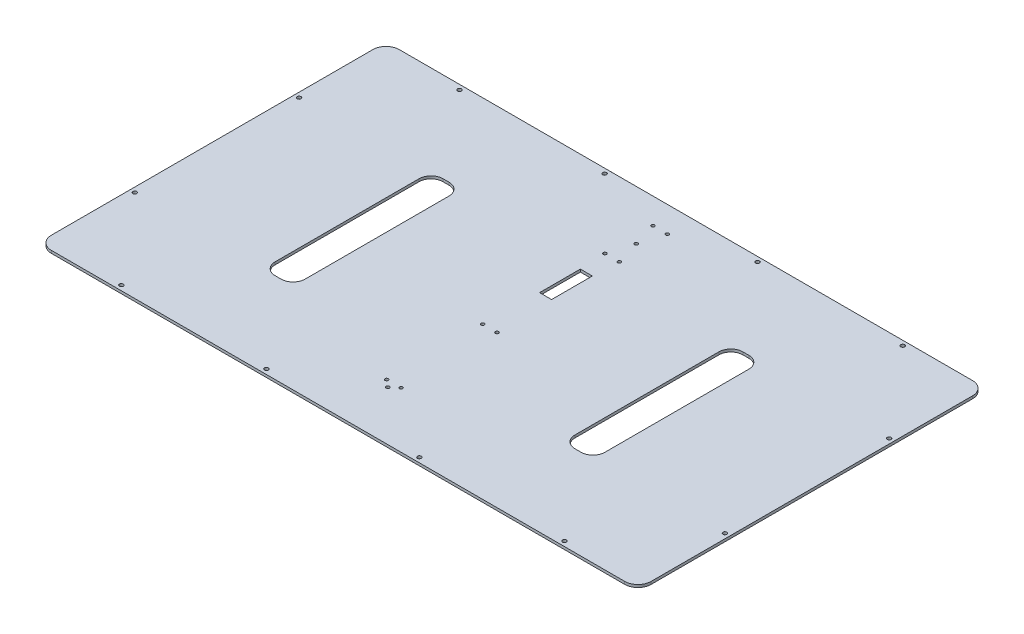
SolidWorks part; units mm, degrees
ref_plane "Front Plane" through (0, 0, 0) normal (0, 0, 1) x (1, 0, 0)
ref_plane "Top Plane" through (0, 0, 0) normal (0, 1, 0) x (1, 0, 0)
ref_plane "Right Plane" through (0, 0, 0) normal (1, 0, 0) x (0, 0, -1)
sketch "Sketch1" plane through (0, 0, 0) normal (0, 1, 0) x (1, 0, 0)
  line L0 (0, 145) -> (0, 141) construction
  line L1 (-239, 145) -> (239, 145)
  line L2 (-250, 134) -> (-250, -134)
  line L3 (-239, -145) -> (239, -145)
  line L4 (250, 134) -> (250, -134)
  line L5 (-250, 145) -> (250, -145) construction
  line L6 (-250, -145) -> (250, 145) construction
  line L7 (0, 0) -> (0, 79.598) construction
  line L8 (0, 0) -> (95.4216, 0) construction
  line L9 (-125, 30) -> (-125, -30) construction
  line L10 (-125, -30) -> (125, -30) construction
  line L11 (125, -30) -> (125, 30) construction
  line L12 (0, 62) -> (0, 28) construction
  line L13 (-127.5, -70) -> (-122.5, -70)
  line L14 (-137.5, -60) -> (-137.5, 60)
  line L15 (-127.5, 70) -> (-122.5, 70)
  line L16 (-112.5, -60) -> (-112.5, 60)
  line L17 (-137.5, -70) -> (-112.5, 70) construction
  line L18 (-137.5, 70) -> (-112.5, -70) construction
  line L19 (122.5, -70) -> (127.5, -70)
  line L20 (112.5, -60) -> (112.5, 60)
  line L21 (122.5, 70) -> (127.5, 70)
  line L22 (137.5, -60) -> (137.5, 60)
  line L23 (112.5, -70) -> (137.5, 70) construction
  line L24 (112.5, 70) -> (137.5, -70) construction
  line L25 (-5, 28) -> (5, 28)
  line L26 (-5, 28) -> (-5, 62)
  line L27 (-5, 62) -> (5, 62)
  line L28 (5, 28) -> (5, 62)
  line L29 (-5, 28) -> (5, 62) construction
  line L30 (-5, 62) -> (5, 28) construction
  arc A0 (-250, -134) -> (-239, -145) centre (-239, -134) ccw
  arc A1 (250, -134) -> (239, -145) centre (239, -134) cw
  arc A2 (250, 134) -> (239, 145) centre (239, 134) ccw
  arc A3 (-239, 145) -> (-250, 134) centre (-239, 134) ccw
  circle A4 centre (63.75, 141) radius 1.6
  circle A5 centre (184.75, 141) radius 1.6
  circle A6 centre (246, 68.5) radius 1.6
  circle A7 centre (0, 103.5) radius 1.4
  circle A8 centre (0, -103.5) radius 1.4
  arc A9 (137.5, 60) -> (127.5, 70) centre (127.5, 60) ccw
  arc A10 (122.5, 70) -> (112.5, 60) centre (122.5, 60) ccw
  arc A11 (137.5, -60) -> (127.5, -70) centre (127.5, -60) cw
  arc A12 (112.5, -60) -> (122.5, -70) centre (122.5, -60) ccw
  arc A13 (-112.5, -60) -> (-122.5, -70) centre (-122.5, -60) cw
  arc A14 (-127.5, -70) -> (-137.5, -60) centre (-127.5, -60) cw
  arc A15 (-112.5, 60) -> (-122.5, 70) centre (-122.5, 60) ccw
  arc A16 (-127.5, 70) -> (-137.5, 60) centre (-127.5, 60) ccw
  circle A17 centre (-246, 68.5) radius 1.6
  circle A18 centre (-184.75, 141) radius 1.6
  circle A19 centre (-63.75, 141) radius 1.6
  circle A20 centre (184.75, -141) radius 1.6
  circle A21 centre (246, -68.5) radius 1.6
  circle A22 centre (63.75, -141) radius 1.6
  circle A23 centre (-63.75, -141) radius 1.6
  circle A24 centre (-184.75, -141) radius 1.6
  circle A25 centre (-246, -68.5) radius 1.6
  point P0 (0, 0)
  point P34 (-125, 0)
  point P41 (125, 0)
  point P76 (0, 45)
  dimension "D3" = 11
  dimension "D8" = 10
  dimension "D1" = 290
  dimension "D2" = 500
  dimension "D4" = 140
  dimension "D5" = 140
  dimension "D6" = 25
  dimension "D7" = 25
  dimension "D9" = 10
  dimension "D10" = 34
extrude "Boss-Extrude1" add sketch "Sketch1" along normal blind 2.2
sketch "Sketch2" plane through (0, 2.2, 0) normal (0, 1, 0) x (1, 0, 0)
  line L0 (0, 62) -> (0, 145) construction
  line L1 (5, 62) -> (-5, 62) construction
  line L2 (239, 145) -> (-239, 145) construction
  line L3 (0, 28) -> (0, -145) construction
  line L4 (-5, 28) -> (5, 28) construction
  line L5 (-239, -145) -> (239, -145) construction
  line L7 (-6, -98.5) -> (6, -98.5) construction
  line L8 (-6, -98.5) -> (-6, -18.5) construction
  line L9 (-6, -18.5) -> (6, -18.5) construction
  line L10 (6, -98.5) -> (6, -18.5) construction
  line L11 (-6, -98.5) -> (6, -18.5) construction
  line L12 (-6, -18.5) -> (6, -98.5) construction
  line L13 (-6, 83.5) -> (6, 83.5) construction
  line L14 (-6, 83.5) -> (-6, 123.5) construction
  line L15 (-6, 123.5) -> (6, 123.5) construction
  line L16 (6, 83.5) -> (6, 123.5) construction
  line L17 (-6, 83.5) -> (6, 123.5) construction
  line L18 (-6, 123.5) -> (6, 83.5) construction
  circle A0 centre (-6, -18.5) radius 1.35
  circle A1 centre (6, -18.5) radius 1.35
  circle A2 centre (-6, -98.5) radius 1.35
  circle A3 centre (6, -98.5) radius 1.35
  circle A4 centre (-6, 123.5) radius 1.35
  circle A5 centre (6, 123.5) radius 1.35
  circle A6 centre (-6, 83.5) radius 1.35
  circle A7 centre (6, 83.5) radius 1.35
  point P12 (0, -58.5)
  point P21 (0, 103.5)
  dimension "D1" = 12
  dimension "D2" = 40
extrude "Cut-Extrude1" cut sketch "Sketch2" against normal blind 59.2
